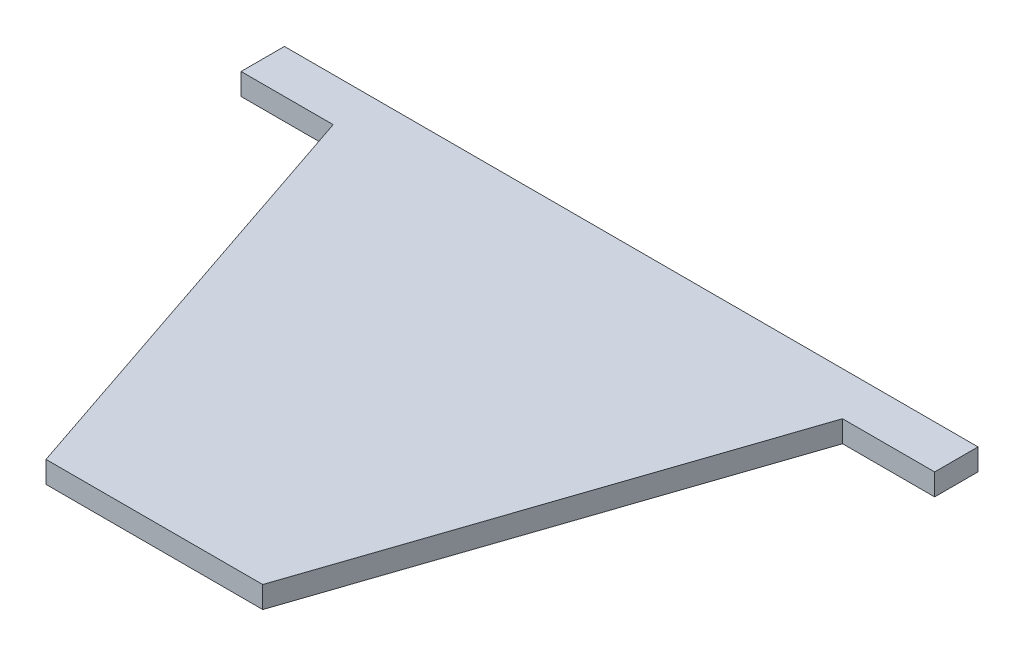
SolidWorks part; units mm, degrees
material "Pin"
ref_plane "Front" through (0, 0, 0) normal (0, 0, 1) x (1, 0, 0)
ref_plane "Top" through (0, 0, 0) normal (0, 1, 0) x (1, 0, 0)
ref_plane "Right" through (0, 0, 0) normal (1, 0, 0) x (0, 0, -1)
sketch "Esquisse1" plane through (0, 0, 0) normal (0, 1, 0) x (1, 0, 0)
  line L2 (-101.6, 139.7) -> (-101.6, 127)
  line L3 (-101.6, 127) -> (-74.6125, 127)
  line L4 (-74.6125, 127) -> (-31.75, 0)
  line L10 (0, 0) -> (0, 155.6258) construction
  line L12 (74.6125, 127) -> (31.75, 0)
  line L13 (101.6, 127) -> (74.6125, 127)
  line L14 (101.6, 139.7) -> (101.6, 127)
  line L18 (-101.6, 139.7) -> (101.6, 139.7)
  line L19 (-31.75, 0) -> (31.75, 0)
  point P6 (-88.1063, 127)
  dimension "D1" = 12.7
  dimension "D2" = 101.6
  dimension "D3" = 63.5
  dimension "D5" = 127
  dimension "D8" = 26.9875
extrude "Boss.-Extru.1" add sketch "Esquisse1" along normal blind 6.35
sketch "Esquisse2" plane through (0, 6.35, 0) normal (0, 1, 0) x (1, 0, 0)
  line L1 (-74.6125, 127) -> (-31.75, 0) construction
  text T0 "<b>BartendUS</b>" font "Britannic Bold" height 15.24
  point P1 (-38.9608, 90.5549)
  point P2 (-54.5451, 77.6422)
  point P3 (-47.4209, 77.8648)
  point P4 (-33.395, 84.3212)
  point P5 (-50.3151, 82.0948)
  point P6 (-37.4024, 70.2953)
  point P7 (-55.9892, 71.8199)
  point P8 (-49.4246, 74.08)
  point P10 (-56.4741, 73.2565)
  dimension "D1" = 2.54
